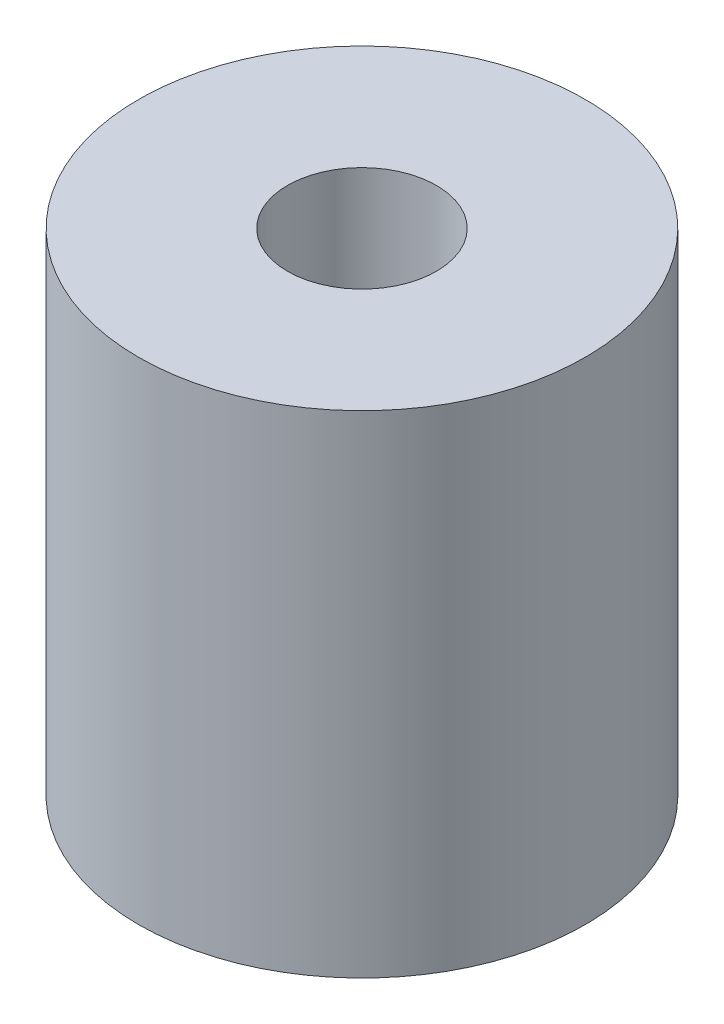
SolidWorks part; units mm, degrees
material "BUTYL"
ref_plane "Front Plane" through (0, 0, 0) normal (0, 0, 1) x (1, 0, 0)
ref_plane "Top Plane" through (0, 0, 0) normal (0, 1, 0) x (1, 0, 0)
ref_plane "Right Plane" through (0, 0, 0) normal (1, 0, 0) x (0, 0, -1)
sketch "Sketch1" plane through (0, 0, 0) normal (0, 1, 0) x (1, 0, 0)
  circle A0 centre (0, 0) radius 3
  circle A1 centre (0, 0) radius 1
  dimension "D1" = 6
  dimension "D2" = 2
extrude "Boss-Extrude1" add sketch "Sketch1" along normal blind 6.6
